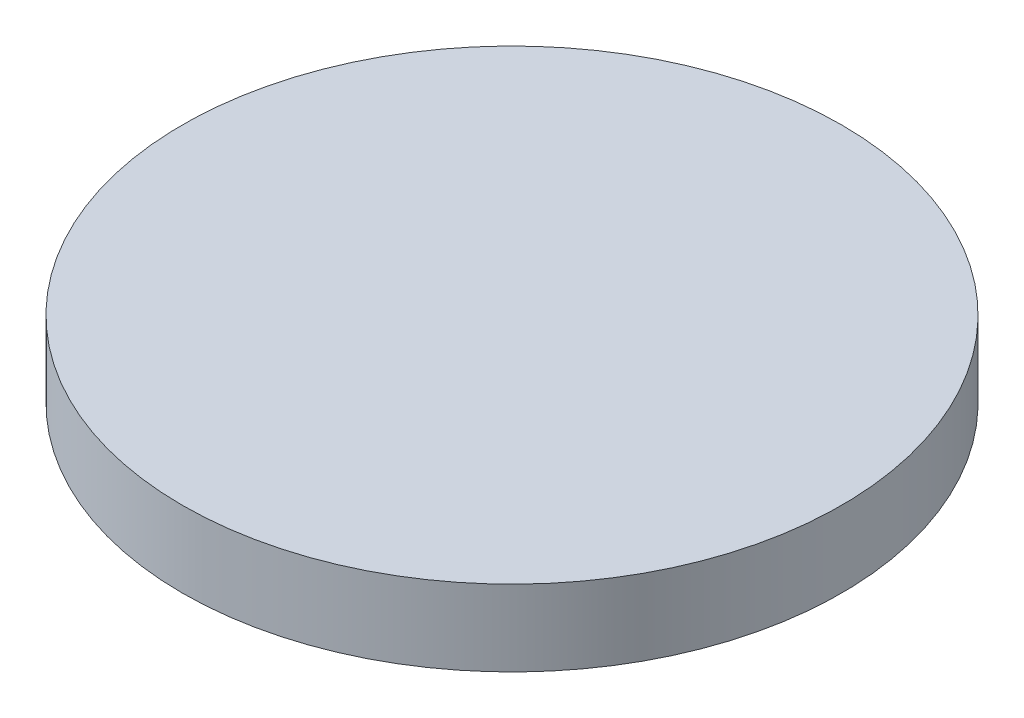
SolidWorks part; units mm, degrees
ref_plane "Спереди" through (0, 0, 0) normal (0, 0, 1) x (1, 0, 0)
ref_plane "Сверху" through (0, 0, 0) normal (0, 1, 0) x (1, 0, 0)
ref_plane "Справа" through (0, 0, 0) normal (1, 0, 0) x (0, 0, -1)
other "Configuration Table"
sketch "Эскиз1" plane through (0, 0, 0) normal (0, 1, 0) x (1, 0, 0)
  circle A0 centre (0, 0) radius 130
  dimension "D1" = 260
extrude "Бобышка-Вытянуть1" add sketch "Эскиз1" along normal blind 30
